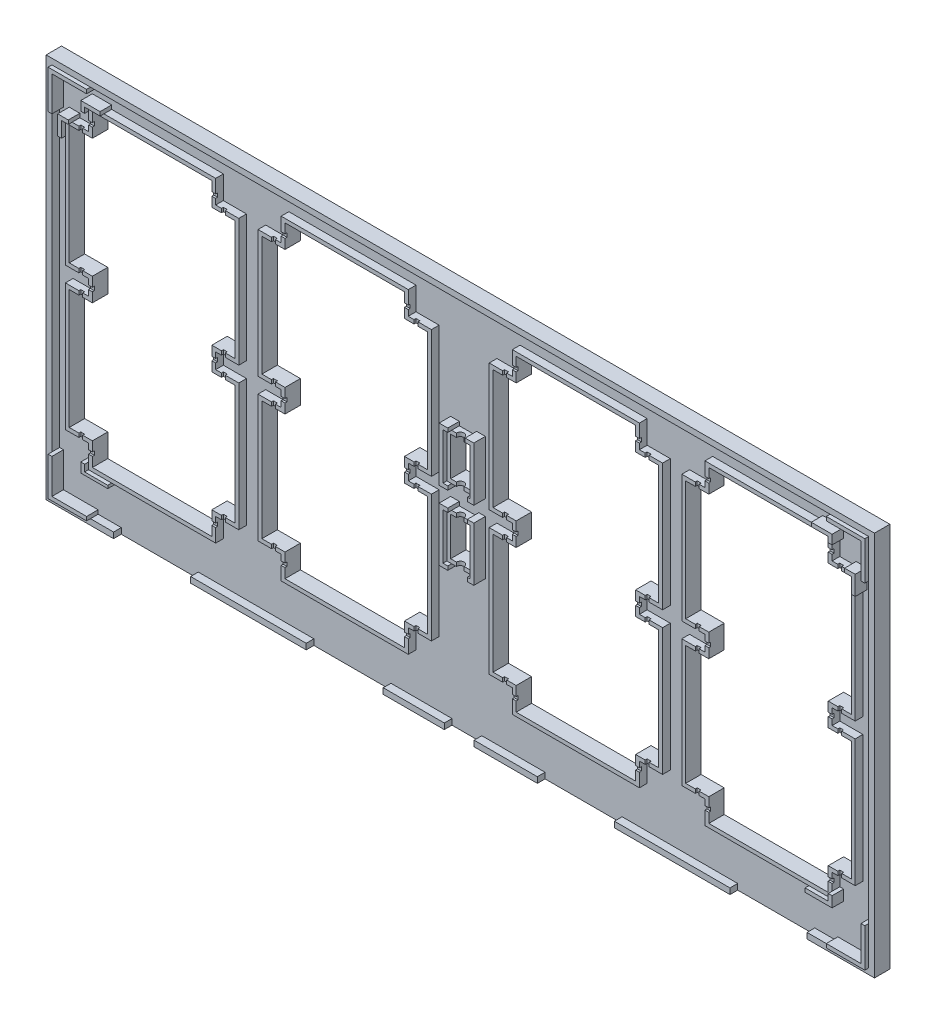
SolidWorks part; units mm, degrees
ref_plane "Спереди" through (0, 0, 0) normal (0, 0, 1) x (1, 0, 0)
ref_plane "Сверху" through (0, 0, 0) normal (0, 1, 0) x (1, 0, 0)
ref_plane "Справа" through (0, 0, 0) normal (1, 0, 0) x (0, 0, -1)
other "Configuration Table"
sketch "Эскиз1" plane through (0, 0, 0) normal (0, 0, 1) x (1, 0, 0)
  line L0 (0, 0) -> (210, 0)
  line L1 (210, 0) -> (210, 100)
  line L2 (210, 100) -> (0, 100)
  line L3 (0, 100) -> (0, 0)
  dimension "D1" = 210
  dimension "D2" = 100
extrude "Бобышка-Вытянуть1" add sketch "Эскиз1" along normal blind 2
sketch "Эскиз2" plane through (0, 0, 2) normal (0, 0, 1) x (1, 0, 0)
  line L4 (3.5, 56.2516) -> (9.5, 56.2516)
  line L5 (40.5, 87.2516) -> (46.5, 87.2516)
  line L6 (9.5, 56.2516) -> (9.5, 50.2516)
  line L7 (9.5, 93.2516) -> (9.5, 87.2516)
  line L9 (40.5, 87.2516) -> (40.5, 93.2516)
  line L10 (40.5, 93.2516) -> (9.5, 93.2516)
  line L11 (53.5, 56.2516) -> (59.5, 56.2516)
  line L12 (9.5, 19.2516) -> (9.5, 13.2516)
  line L13 (9.5, 13.2516) -> (40.5, 13.2516)
  line L14 (40.5, 13.2516) -> (40.5, 19.2516)
  line L16 (90.5, 87.2516) -> (96.5, 87.2516)
  line L20 (40.5, 56.2516) -> (40.5, 50.2516)
  line L21 (59.5, 56.2516) -> (59.5, 50.2516)
  line L22 (59.5, 93.2516) -> (59.5, 87.2516)
  line L23 (25, 93.2516) -> (25, 13.3713) construction
  line L24 (25, 56.2516) -> (25, 33.3628) construction
  line L25 (3.5, 50.2516) -> (3.5, 19.2516)
  line L26 (3.5, 19.2516) -> (9.5, 19.2516)
  line L28 (9.5, 50.2516) -> (3.5, 50.2516)
  line L30 (40.5, 56.2516) -> (46.5, 56.2516)
  line L31 (46.5, 56.2516) -> (46.5, 87.2516)
  line L33 (3.5, 87.2516) -> (3.5, 56.2516)
  line L36 (9.5, 87.2516) -> (3.5, 87.2516)
  line L38 (40.5, 19.2516) -> (46.5, 19.2516)
  line L39 (46.5, 19.2516) -> (46.5, 50.2516)
  line L40 (46.5, 50.2516) -> (40.5, 50.2516)
  line L41 (25, 19.2516) -> (25, 10.047) construction
  line L42 (6.5, 87.2516) -> (6.5, 54.1946) construction
  line L43 (0, 100) -> (0, 0) construction
  line L45 (90.5, 87.2516) -> (90.5, 93.2516)
  line L46 (90.5, 93.2516) -> (59.5, 93.2516)
  line L47 (59.5, 19.2516) -> (59.5, 13.2516)
  line L48 (59.5, 13.2516) -> (90.5, 13.2516)
  line L49 (90.5, 13.2516) -> (90.5, 19.2516)
  line L53 (90.5, 56.2516) -> (90.5, 50.2516)
  line L54 (53.5, 50.2516) -> (53.5, 19.2516)
  line L55 (53.5, 19.2516) -> (59.5, 19.2516)
  line L57 (59.5, 50.2516) -> (53.5, 50.2516)
  line L59 (90.5, 56.2516) -> (96.5, 56.2516)
  line L60 (96.5, 56.2516) -> (96.5, 87.2516)
  line L61 (53.5, 87.2516) -> (53.5, 56.2516)
  line L63 (59.5, 87.2516) -> (53.5, 87.2516)
  line L65 (90.5, 19.2516) -> (96.5, 19.2516)
  line L66 (96.5, 19.2516) -> (96.5, 50.2516)
  line L67 (96.5, 50.2516) -> (90.5, 50.2516)
  line L68 (75, 93.2516) -> (75, 13.3713) construction
  line L69 (75, 56.2516) -> (75, 33.3628) construction
  line L70 (75, 19.2516) -> (75, 10.047) construction
  line L71 (56.5, 87.2516) -> (56.5, 54.1946) construction
  line L72 (3.5, 56.2516) -> (9.5, 56.2516) construction
  line L73 (113.5, 56.2516) -> (119.5, 56.2516)
  line L74 (150.5, 87.2516) -> (156.5, 87.2516)
  line L75 (119.5, 56.2516) -> (119.5, 50.2516)
  line L76 (119.5, 93.2516) -> (119.5, 87.2516)
  line L78 (150.5, 87.2516) -> (150.5, 93.2516)
  line L79 (150.5, 93.2516) -> (119.5, 93.2516)
  line L80 (119.5, 19.2516) -> (119.5, 13.2516)
  line L81 (119.5, 13.2516) -> (150.5, 13.2516)
  line L82 (150.5, 13.2516) -> (150.5, 19.2516)
  line L86 (150.5, 56.2516) -> (150.5, 50.2516)
  line L87 (113.5, 50.2516) -> (113.5, 19.2516)
  line L88 (113.5, 19.2516) -> (119.5, 19.2516)
  line L90 (119.5, 50.2516) -> (113.5, 50.2516)
  line L92 (150.5, 56.2516) -> (156.5, 56.2516)
  line L93 (156.5, 56.2516) -> (156.5, 87.2516)
  line L94 (113.5, 87.2516) -> (113.5, 56.2516)
  line L96 (119.5, 87.2516) -> (113.5, 87.2516)
  line L98 (150.5, 19.2516) -> (156.5, 19.2516)
  line L99 (156.5, 19.2516) -> (156.5, 50.2516)
  line L100 (156.5, 50.2516) -> (150.5, 50.2516)
  line L101 (135, 93.2516) -> (135, 13.3713) construction
  line L102 (135, 56.2516) -> (135, 33.3628) construction
  line L103 (135, 19.2516) -> (135, 10.047) construction
  line L104 (116.5, 87.2516) -> (116.5, 54.1946) construction
  line L105 (90.5, 56.2516) -> (96.5, 56.2516) construction
  line L106 (53.5, 56.2516) -> (59.5, 56.2516) construction
  line L107 (163.5, 56.2516) -> (169.5, 56.2516)
  line L108 (200.5, 87.2516) -> (206.5, 87.2516)
  line L109 (169.5, 56.2516) -> (169.5, 50.2516)
  line L110 (169.5, 93.2516) -> (169.5, 87.2516)
  line L112 (200.5, 87.2516) -> (200.5, 93.2516)
  line L113 (200.5, 93.2516) -> (169.5, 93.2516)
  line L114 (169.5, 19.2516) -> (169.5, 13.2516)
  line L115 (169.5, 13.2516) -> (200.5, 13.2516)
  line L116 (200.5, 13.2516) -> (200.5, 19.2516)
  line L120 (200.5, 56.2516) -> (200.5, 50.2516)
  line L121 (163.5, 50.2516) -> (163.5, 19.2516)
  line L122 (163.5, 19.2516) -> (169.5, 19.2516)
  line L124 (169.5, 50.2516) -> (163.5, 50.2516)
  line L126 (200.5, 56.2516) -> (206.5, 56.2516)
  line L127 (206.5, 56.2516) -> (206.5, 87.2516)
  line L128 (163.5, 87.2516) -> (163.5, 56.2516)
  line L130 (169.5, 87.2516) -> (163.5, 87.2516)
  line L132 (200.5, 19.2516) -> (206.5, 19.2516)
  line L133 (206.5, 19.2516) -> (206.5, 50.2516)
  line L134 (206.5, 50.2516) -> (200.5, 50.2516)
  line L135 (185, 93.2516) -> (185, 13.3713) construction
  line L136 (185, 56.2516) -> (185, 33.3628) construction
  line L137 (185, 19.2516) -> (185, 10.047) construction
  line L138 (166.5, 87.2516) -> (166.5, 54.1946) construction
  line L139 (113.5, 56.2516) -> (119.5, 56.2516) construction
  line L140 (113.5, 56.2516) -> (119.5, 56.2516) construction
  line L141 (113.5, 56.2516) -> (119.5, 56.2516) construction
  line L142 (40.5, 56.2516) -> (46.5, 56.2516) construction
  line L143 (90.5, 56.2516) -> (96.5, 56.2516) construction
  line L144 (150.5, 56.2516) -> (156.5, 56.2516) construction
  line L145 (150.5, 56.2516) -> (156.5, 56.2516) construction
  line L146 (150.5, 56.2516) -> (156.5, 56.2516) construction
  point P0 (0, 0)
  dimension "D3" = 25
  dimension "D4" = 25
  dimension "D5" = 2
  dimension "D6" = 31
  dimension "D7" = 31
  dimension "D8" = 18.5
  dimension "D9" = 6
  dimension "D10" = 6
  dimension "D12" = 2
  dimension "D13" = 60
  dimension "D14" = 2
  dimension "D15" = 31
  dimension "D16" = 6
  dimension "D23" = 6
  dimension "D24" = 6
  dimension "D25" = 6
extrude "Вырез-Вытянуть1" cut sketch "Эскиз2" against normal blind 2 contours L11 L21 L57 L54 L55 L47 L48 L49 L65 L66 L67 L53 L59 L60 L16 L45 L46 L22 L63 L61 | L96 L94 L73 L75 L90 L87 L88 L80 L81 L82 L98 L99 L100 L86 L92 L93 L74 L78 L79 L76 | L12 L13 L14 L38 L39 L40 L20 L30 L31 L5 L9 L10 L7 L36 L33 L4 L6 L28 L25 L26 | L120 L126 L127 L108 L112 L113 L110 L130 L128 L107 L109 L124 L121 L122 L114 L115 L116 L132 L133 L134
sketch "Эскиз3" plane through (0, 0, 2) normal (0, 0, 1) x (1, 0, 0)
  line L0 (105, 100) -> (105, 0) construction
  line L1 (210, 100) -> (0, 100) construction
  line L2 (0, 0) -> (210, 0) construction
  line L3 (102.5, 67.2516) -> (107.5, 67.2516)
  line L4 (107.5, 67.2516) -> (107.5, 57.2516)
  line L5 (107.5, 57.2516) -> (102.5, 57.2516)
  line L6 (102.5, 57.2516) -> (102.5, 67.2516)
  line L7 (102.5, 49.2516) -> (102.5, 39.2516)
  line L8 (102.5, 39.2516) -> (107.5, 39.2516)
  line L10 (107.5, 49.2516) -> (102.5, 49.2516)
  line L11 (107.5, 49.2516) -> (107.5, 39.2516)
  line L13 (113.5, 56.2516) -> (119.5, 56.2516) construction
  point P14 (107.5, 62.2516)
  dimension "D1" = 10
  dimension "D2" = 5
  dimension "D3" = 5
  dimension "D4" = 10
  dimension "D5" = 2.5
  dimension "D6" = 8
  dimension "D7" = 1
extrude "Вырез-Вытянуть2" cut sketch "Эскиз3" against normal blind 2
sketch "Эскиз5" plane through (0, 0, 2) normal (0, 0, 1) x (1, 0, 0)
  line L0 (9.5, 93.2516) -> (40.5, 93.2516)
  line L1 (40.5, 93.2516) -> (40.5, 87.2516)
  line L2 (40.5, 87.2516) -> (46.5, 87.2516)
  line L3 (46.5, 87.2516) -> (46.5, 56.2516)
  line L4 (46.5, 56.2516) -> (40.5, 56.2516)
  line L5 (40.5, 56.2516) -> (40.5, 50.2516)
  line L6 (40.5, 50.2516) -> (46.5, 50.2516)
  line L7 (46.5, 50.2516) -> (46.5, 19.2516)
  line L8 (46.5, 19.2516) -> (40.5, 19.2516)
  line L9 (40.5, 19.2516) -> (40.5, 13.2516)
  line L10 (40.5, 13.2516) -> (9.5, 13.2516)
  line L11 (9.5, 13.2516) -> (9.5, 19.2516)
  line L12 (9.5, 19.2516) -> (3.5, 19.2516)
  line L13 (3.5, 19.2516) -> (3.5, 50.2516)
  line L14 (3.5, 50.2516) -> (9.5, 50.2516)
  line L15 (9.5, 50.2516) -> (9.5, 56.2516)
  line L16 (9.5, 56.2516) -> (3.5, 56.2516)
  line L17 (3.5, 56.2516) -> (3.5, 87.2516)
  line L18 (3.5, 87.2516) -> (9.5, 87.2516)
  line L19 (9.5, 87.2516) -> (9.5, 93.2516)
  line L20 (8.5, 88.2516) -> (8.5, 94.2516)
  line L21 (8.5, 94.2516) -> (41.5, 94.2516)
  line L22 (41.5, 94.2516) -> (41.5, 88.2516)
  line L23 (41.5, 88.2516) -> (47.5, 88.2516)
  line L24 (47.5, 88.2516) -> (47.5, 55.2516)
  line L25 (47.5, 55.2516) -> (41.5, 55.2516)
  line L26 (41.5, 55.2516) -> (41.5, 51.2516)
  line L27 (41.5, 51.2516) -> (47.5, 51.2516)
  line L28 (47.5, 51.2516) -> (47.5, 18.2516)
  line L29 (47.5, 18.2516) -> (41.5, 18.2516)
  line L30 (41.5, 18.2516) -> (41.5, 12.2516)
  line L31 (41.5, 12.2516) -> (8.5, 12.2516)
  line L32 (8.5, 12.2516) -> (8.5, 18.2516)
  line L33 (8.5, 18.2516) -> (2.5, 18.2516)
  line L34 (2.5, 18.2516) -> (2.5, 51.2516)
  line L35 (2.5, 51.2516) -> (8.5, 51.2516)
  line L36 (8.5, 51.2516) -> (8.5, 55.2516)
  line L37 (8.5, 55.2516) -> (2.5, 55.2516)
  line L38 (2.5, 55.2516) -> (2.5, 88.2516)
  line L39 (2.5, 88.2516) -> (8.5, 88.2516)
  dimension "D1" = 1
extrude "Бобышка-Вытянуть3" add sketch "Эскиз5" along normal blind 2
sketch "Эскиз6" plane through (0, 0, 2) normal (0, 0, 1) x (1, 0, 0)
  line L0 (59.5, 93.2516) -> (90.5, 93.2516)
  line L1 (90.5, 93.2516) -> (90.5, 87.2516)
  line L2 (90.5, 87.2516) -> (96.5, 87.2516)
  line L3 (96.5, 87.2516) -> (96.5, 56.2516)
  line L4 (96.5, 56.2516) -> (90.5, 56.2516)
  line L5 (90.5, 56.2516) -> (90.5, 50.2516)
  line L6 (90.5, 50.2516) -> (96.5, 50.2516)
  line L7 (96.5, 50.2516) -> (96.5, 19.2516)
  line L8 (96.5, 19.2516) -> (90.5, 19.2516)
  line L9 (90.5, 19.2516) -> (90.5, 13.2516)
  line L10 (90.5, 13.2516) -> (59.5, 13.2516)
  line L11 (59.5, 13.2516) -> (59.5, 19.2516)
  line L12 (59.5, 19.2516) -> (53.5, 19.2516)
  line L13 (53.5, 19.2516) -> (53.5, 50.2516)
  line L14 (53.5, 50.2516) -> (59.5, 50.2516)
  line L15 (59.5, 50.2516) -> (59.5, 56.2516)
  line L16 (53.5, 56.2516) -> (59.5, 56.2516) construction
  line L17 (59.5, 56.2516) -> (59.5, 50.2516) construction
  line L18 (59.5, 56.2516) -> (53.5, 56.2516)
  line L19 (53.5, 56.2516) -> (53.5, 87.2516)
  line L20 (53.5, 87.2516) -> (59.5, 87.2516)
  line L21 (59.5, 87.2516) -> (59.5, 93.2516)
  line L22 (58.5, 88.2516) -> (58.5, 94.2516)
  line L23 (58.5, 94.2516) -> (91.5, 94.2516)
  line L24 (91.5, 94.2516) -> (91.5, 88.2516)
  line L25 (91.5, 88.2516) -> (97.5, 88.2516)
  line L26 (97.5, 88.2516) -> (97.5, 55.2516)
  line L27 (97.5, 55.2516) -> (91.5, 55.2516)
  line L28 (91.5, 55.2516) -> (91.5, 51.2516)
  line L29 (91.5, 51.2516) -> (97.5, 51.2516)
  line L30 (97.5, 51.2516) -> (97.5, 18.2516)
  line L31 (97.5, 18.2516) -> (91.5, 18.2516)
  line L32 (91.5, 18.2516) -> (91.5, 12.2516)
  line L33 (91.5, 12.2516) -> (58.5, 12.2516)
  line L34 (58.5, 12.2516) -> (58.5, 18.2516)
  line L35 (58.5, 18.2516) -> (52.5, 18.2516)
  line L36 (52.5, 18.2516) -> (52.5, 51.2516)
  line L37 (52.5, 51.2516) -> (58.5, 51.2516)
  line L38 (58.5, 51.2516) -> (58.5, 55.2516)
  line L39 (58.5, 55.2516) -> (52.5, 55.2516)
  line L40 (52.5, 55.2516) -> (52.5, 88.2516)
  line L41 (52.5, 88.2516) -> (58.5, 88.2516)
  dimension "D1" = 1
extrude "Бобышка-Вытянуть4" add sketch "Эскиз6" along normal blind 2
sketch "Эскиз7" plane through (0, 0, 2) normal (0, 0, 1) x (1, 0, 0)
  line L0 (0, 100) -> (-2.5, 100)
  line L1 (-2.5, 100) -> (-2.5, 0)
  line L2 (-2.5, 0) -> (0, 0)
  line L3 (0, 0) -> (0, 100)
  dimension "D1" = 2.5
extrude "Бобышка-Вытянуть5" add sketch "Эскиз7" against normal blind 2
sketch "Эскиз8" plane through (0, 0, 2) normal (0, 0, 1) x (1, 0, 0)
  line L0 (210, 100) -> (212.5, 100)
  line L1 (212.5, 100) -> (212.5, 0)
  line L2 (212.5, 0) -> (210, 0)
  line L3 (210, 0) -> (210, 100)
  dimension "D1" = 2.5
extrude "Бобышка-Вытянуть6" add sketch "Эскиз8" against normal blind 2
sketch "Эскиз9" plane through (0, 0, 2) normal (0, 0, 1) x (1, 0, 0)
  line L0 (102.5, 67.2516) -> (107.5, 67.2516)
  line L1 (107.5, 67.2516) -> (107.5, 57.2516)
  line L2 (107.5, 57.2516) -> (102.5, 57.2516)
  line L3 (102.5, 57.2516) -> (102.5, 67.2516)
  line L4 (101.5, 56.2516) -> (101.5, 68.2516)
  line L5 (101.5, 68.2516) -> (108.5, 68.2516)
  line L6 (108.5, 68.2516) -> (108.5, 56.2516)
  line L7 (108.5, 56.2516) -> (101.5, 56.2516)
  dimension "D1" = 1
extrude "Бобышка-Вытянуть7" add sketch "Эскиз9" along normal blind 2
sketch "Эскиз10" plane through (0, 0, 2) normal (0, 0, 1) x (1, 0, 0)
  line L0 (102.5, 49.2516) -> (107.5, 49.2516)
  line L1 (107.5, 49.2516) -> (107.5, 39.2516)
  line L2 (107.5, 39.2516) -> (102.5, 39.2516)
  line L3 (102.5, 39.2516) -> (102.5, 49.2516)
  line L4 (101.5, 38.2516) -> (101.5, 50.2516)
  line L5 (101.5, 50.2516) -> (108.5, 50.2516)
  line L6 (108.5, 50.2516) -> (108.5, 38.2516)
  line L7 (108.5, 38.2516) -> (101.5, 38.2516)
  dimension "D1" = 1
extrude "Бобышка-Вытянуть8" add sketch "Эскиз10" along normal blind 2
sketch "Эскиз11" plane through (0, 0, 2) normal (0, 0, 1) x (1, 0, 0)
  line L0 (119.5, 93.2516) -> (150.5, 93.2516)
  line L1 (150.5, 93.2516) -> (150.5, 87.2516)
  line L2 (150.5, 87.2516) -> (156.5, 87.2516)
  line L3 (156.5, 87.2516) -> (156.5, 56.2516)
  line L4 (156.5, 56.2516) -> (150.5, 56.2516)
  line L5 (150.5, 56.2516) -> (150.5, 50.2516)
  line L6 (150.5, 50.2516) -> (156.5, 50.2516)
  line L7 (156.5, 50.2516) -> (156.5, 19.2516)
  line L8 (156.5, 19.2516) -> (150.5, 19.2516)
  line L9 (150.5, 19.2516) -> (150.5, 13.2516)
  line L10 (150.5, 13.2516) -> (119.5, 13.2516)
  line L11 (119.5, 13.2516) -> (119.5, 19.2516)
  line L12 (119.5, 19.2516) -> (113.5, 19.2516)
  line L13 (113.5, 19.2516) -> (113.5, 50.2516)
  line L14 (113.5, 50.2516) -> (119.5, 50.2516)
  line L15 (119.5, 50.2516) -> (119.5, 56.2516)
  line L16 (119.5, 56.2516) -> (113.5, 56.2516)
  line L17 (113.5, 56.2516) -> (113.5, 87.2516)
  line L18 (113.5, 87.2516) -> (119.5, 87.2516)
  line L19 (119.5, 87.2516) -> (119.5, 93.2516)
  line L20 (118.5, 88.2516) -> (118.5, 94.2516)
  line L21 (118.5, 94.2516) -> (151.5, 94.2516)
  line L22 (151.5, 94.2516) -> (151.5, 88.2516)
  line L23 (151.5, 88.2516) -> (157.5, 88.2516)
  line L24 (157.5, 88.2516) -> (157.5, 55.2516)
  line L25 (157.5, 55.2516) -> (151.5, 55.2516)
  line L26 (151.5, 55.2516) -> (151.5, 51.2516)
  line L27 (151.5, 51.2516) -> (157.5, 51.2516)
  line L28 (157.5, 51.2516) -> (157.5, 18.2516)
  line L29 (157.5, 18.2516) -> (151.5, 18.2516)
  line L30 (151.5, 18.2516) -> (151.5, 12.2516)
  line L31 (151.5, 12.2516) -> (118.5, 12.2516)
  line L32 (118.5, 12.2516) -> (118.5, 18.2516)
  line L33 (118.5, 18.2516) -> (112.5, 18.2516)
  line L34 (112.5, 18.2516) -> (112.5, 51.2516)
  line L35 (112.5, 51.2516) -> (118.5, 51.2516)
  line L36 (118.5, 51.2516) -> (118.5, 55.2516)
  line L37 (118.5, 55.2516) -> (112.5, 55.2516)
  line L38 (112.5, 55.2516) -> (112.5, 88.2516)
  line L39 (112.5, 88.2516) -> (118.5, 88.2516)
  dimension "D1" = 1
extrude "Бобышка-Вытянуть9" add sketch "Эскиз11" along normal blind 2
sketch "Эскиз12" plane through (0, 0, 2) normal (0, 0, 1) x (1, 0, 0)
  line L0 (169.5, 93.2516) -> (200.5, 93.2516)
  line L1 (200.5, 93.2516) -> (200.5, 87.2516)
  line L2 (200.5, 87.2516) -> (206.5, 87.2516)
  line L3 (206.5, 87.2516) -> (206.5, 56.2516)
  line L4 (206.5, 56.2516) -> (200.5, 56.2516)
  line L5 (200.5, 56.2516) -> (200.5, 50.2516)
  line L6 (200.5, 50.2516) -> (206.5, 50.2516)
  line L7 (206.5, 50.2516) -> (206.5, 19.2516)
  line L8 (206.5, 19.2516) -> (200.5, 19.2516)
  line L9 (200.5, 19.2516) -> (200.5, 13.2516)
  line L10 (200.5, 13.2516) -> (169.5, 13.2516)
  line L11 (169.5, 13.2516) -> (169.5, 19.2516)
  line L12 (169.5, 19.2516) -> (163.5, 19.2516)
  line L13 (163.5, 19.2516) -> (163.5, 50.2516)
  line L14 (163.5, 50.2516) -> (169.5, 50.2516)
  line L15 (169.5, 50.2516) -> (169.5, 56.2516)
  line L16 (163.5, 56.2516) -> (169.5, 56.2516) construction
  line L17 (169.5, 56.2516) -> (169.5, 50.2516) construction
  line L18 (169.5, 56.2516) -> (163.5, 56.2516)
  line L19 (163.5, 56.2516) -> (163.5, 87.2516)
  line L20 (163.5, 87.2516) -> (169.5, 87.2516)
  line L21 (169.5, 87.2516) -> (169.5, 93.2516)
  line L22 (168.5, 88.2516) -> (168.5, 94.2516)
  line L23 (168.5, 94.2516) -> (201.5, 94.2516)
  line L24 (201.5, 94.2516) -> (201.5, 88.2516)
  line L25 (201.5, 88.2516) -> (207.5, 88.2516)
  line L26 (207.5, 88.2516) -> (207.5, 55.2516)
  line L27 (207.5, 55.2516) -> (201.5, 55.2516)
  line L28 (201.5, 55.2516) -> (201.5, 51.2516)
  line L29 (201.5, 51.2516) -> (207.5, 51.2516)
  line L30 (207.5, 51.2516) -> (207.5, 18.2516)
  line L31 (207.5, 18.2516) -> (201.5, 18.2516)
  line L32 (201.5, 18.2516) -> (201.5, 12.2516)
  line L33 (201.5, 12.2516) -> (168.5, 12.2516)
  line L34 (168.5, 12.2516) -> (168.5, 18.2516)
  line L35 (168.5, 18.2516) -> (162.5, 18.2516)
  line L36 (162.5, 18.2516) -> (162.5, 51.2516)
  line L37 (162.5, 51.2516) -> (168.5, 51.2516)
  line L38 (168.5, 51.2516) -> (168.5, 55.2516)
  line L39 (168.5, 55.2516) -> (162.5, 55.2516)
  line L40 (162.5, 55.2516) -> (162.5, 88.2516)
  line L41 (162.5, 88.2516) -> (168.5, 88.2516)
  dimension "D1" = 1
extrude "Бобышка-Вытянуть10" add sketch "Эскиз12" along normal blind 2
sketch "Эскиз13" plane through (0, 0, 2) normal (0, 0, 1) x (1, 0, 0)
  line L0 (-1, 98.5) -> (211, 98.5)
  line L1 (-2.5, 100) -> (212.5, 100)
  line L2 (212.5, 100) -> (212.5, 0)
  line L3 (212.5, 0) -> (-2.5, 0)
  line L4 (-2.5, 0) -> (-2.5, 100)
  line L5 (211, 98.5) -> (211, 1.5)
  line L6 (211, 1.5) -> (-1, 1.5)
  line L7 (-1, 1.5) -> (-1, 98.5)
  dimension "D1" = 1.5
extrude "Бобышка-Вытянуть12" add sketch "Эскиз13" along normal blind 2
sketch "Эскиз15" plane through (0, 0, 4) normal (0, 0, 1) x (1, 0, 0)
  line L0 (6.5, 87.2516) -> (6.5, 19.2516) construction
  line L1 (9.5, 87.2516) -> (3.5, 87.2516) construction
  line L2 (3.5, 19.2516) -> (9.5, 19.2516) construction
  line L3 (7, 87.8467) -> (7, 16.4283)
  line L4 (7, 16.4283) -> (6, 16.4283)
  line L5 (6, 16.4283) -> (6, 89.7154)
  line L6 (6, 89.7154) -> (7, 89.7154)
  line L7 (7, 89.7154) -> (7, 87.8467)
  dimension "D1" = 0.5
  dimension "D2" = 0.5
extrude "Вырез-Вытянуть5" cut sketch "Эскиз15" against normal blind 0.5
sketch "Эскиз16" plane through (0, 0, 4) normal (0, 0, 1) x (1, 0, 0)
  line L0 (9.5, 53.2516) -> (202.9622, 53.2516) construction
  line L1 (9.5, 56.2516) -> (9.5, 50.2516) construction
  line L2 (9.5, 53.7516) -> (207.2357, 53.7516)
  line L3 (207.2357, 53.7516) -> (207.2357, 52.7516)
  line L4 (207.2357, 52.7516) -> (7.0331, 52.7516)
  line L5 (7.0331, 52.7516) -> (7.0331, 53.7516)
  line L6 (7.0331, 53.7516) -> (9.5, 53.7516)
  dimension "D1" = 0.5
  dimension "D2" = 0.5
extrude "Вырез-Вытянуть6" cut sketch "Эскиз16" against normal blind 0.5
sketch "Эскиз18" plane through (0, 38.2516, 0) normal (0, -1, 0) x (1, 0, 0)
  line L0 (-2.5, 4) -> (212.5, 4) construction
  circle A0 centre (105, 4) radius 1
extrude "Вырез-Вытянуть8" cut sketch "Эскиз18" against normal blind 40
sketch "Эскиз19" plane through (0, 0, 4) normal (0, 0, 1) x (1, 0, 0)
  line L0 (9.5, 16.2516) -> (200.5, 16.2516) construction
  line L1 (9.5, 19.2516) -> (9.5, 13.2516) construction
  line L2 (200.5, 13.2516) -> (200.5, 19.2516) construction
  line L3 (9.5, 16.7516) -> (205.6371, 16.7516)
  line L4 (205.6371, 16.7516) -> (205.6371, 15.7516)
  line L5 (205.6371, 15.7516) -> (6.3461, 15.7516)
  line L6 (6.3461, 15.7516) -> (6.3461, 16.7516)
  line L7 (6.3461, 16.7516) -> (9.5, 16.7516)
  dimension "D1" = 0.5
  dimension "D2" = 0.5
extrude "Вырез-Вытянуть9" cut sketch "Эскиз19" against normal blind 0.5
sketch "Эскиз20" plane through (0, 0, 4) normal (0, 0, 1) x (1, 0, 0)
  line L0 (9.5, 90.2516) -> (204.4151, 90.2516) construction
  line L1 (9.5, 93.2516) -> (9.5, 87.2516) construction
  line L2 (9.5, 90.7516) -> (205.9858, 90.7516)
  line L3 (205.9858, 90.7516) -> (205.9858, 89.7516)
  line L4 (205.9858, 89.7516) -> (6.902, 89.7516)
  line L5 (6.902, 89.7516) -> (6.902, 90.7516)
  line L6 (6.902, 90.7516) -> (9.5, 90.7516)
  dimension "D1" = 0.5
  dimension "D2" = 0.5
extrude "Вырез-Вытянуть10" cut sketch "Эскиз20" against normal blind 0.5
sketch "Эскиз21" plane through (0, 0, 4) normal (0, 0, 1) x (1, 0, 0)
  line L0 (43.5, 19.2516) -> (43.5, 87.2516) construction
  line L1 (40.5, 19.2516) -> (46.5, 19.2516) construction
  line L2 (46.5, 87.2516) -> (40.5, 87.2516) construction
  line L3 (44, 87.2516) -> (44, 14.6693)
  line L4 (44, 14.6693) -> (43, 14.6693)
  line L5 (43, 14.6693) -> (43, 89.404)
  line L6 (43, 89.404) -> (44, 89.404)
  line L7 (44, 89.404) -> (44, 87.2516)
  dimension "D1" = 0.5
  dimension "D2" = 0.5
extrude "Вырез-Вытянуть11" cut sketch "Эскиз21" against normal blind 0.5
sketch "Эскиз22" plane through (0, 0, 4) normal (0, 0, 1) x (1, 0, 0)
  line L0 (56.5, 87.2516) -> (56.5, 19.2516) construction
  line L1 (59.5, 87.2516) -> (53.5, 87.2516) construction
  line L2 (53.5, 19.2516) -> (59.5, 19.2516) construction
  line L3 (57, 87.2516) -> (57, 16.867)
  line L4 (57, 16.867) -> (56, 16.867)
  line L5 (56, 16.867) -> (56, 91.2358)
  line L6 (56, 91.2358) -> (57, 91.2358)
  line L7 (57, 91.2358) -> (57, 87.2516)
  dimension "D1" = 0.5
  dimension "D2" = 0.5
extrude "Вырез-Вытянуть12" cut sketch "Эскиз22" against normal blind 0.5
sketch "Эскиз23" plane through (0, 0, 4) normal (0, 0, 1) x (1, 0, 0)
  line L0 (93.5, 87.2516) -> (93.5, 19.2516) construction
  line L1 (96.5, 87.2516) -> (90.5, 87.2516) construction
  line L2 (90.5, 19.2516) -> (96.5, 19.2516) construction
  line L3 (94, 19.2516) -> (94, 90.8274)
  line L4 (94, 90.8274) -> (93, 90.8274)
  line L5 (93, 90.8274) -> (93, 16.2231)
  line L6 (93, 16.2231) -> (94, 16.2231)
  line L7 (94, 16.2231) -> (94, 19.2516)
  dimension "D1" = 0.5
  dimension "D2" = 0.5
extrude "Вырез-Вытянуть13" cut sketch "Эскиз23" against normal blind 0.5
sketch "Эскиз24" plane through (0, 0, 4) normal (0, 0, 1) x (1, 0, 0)
  line L0 (116.5, 87.2516) -> (116.5, 19.2516) construction
  line L1 (119.5, 87.2516) -> (113.5, 87.2516) construction
  line L2 (113.5, 19.2516) -> (119.5, 19.2516) construction
  line L3 (116, 19.2516) -> (116, 17.2818)
  line L4 (116, 17.2818) -> (117, 17.2818)
  line L5 (117, 17.2818) -> (117, 91.1115)
  line L6 (117, 91.1115) -> (116, 91.1115)
  line L7 (116, 91.1115) -> (116, 19.2516)
  dimension "D1" = 0.5
  dimension "D2" = 0.5
extrude "Вырез-Вытянуть14" cut sketch "Эскиз24" against normal blind 0.5
sketch "Эскиз25" plane through (0, 0, 4) normal (0, 0, 1) x (1, 0, 0)
  line L0 (153.5, 87.2516) -> (153.5, 19.2516) construction
  line L1 (156.5, 87.2516) -> (150.5, 87.2516) construction
  line L2 (150.5, 19.2516) -> (156.5, 19.2516) construction
  line L3 (154, 19.2516) -> (154, 16.4787)
  line L4 (154, 16.4787) -> (153, 16.4787)
  line L5 (153, 16.4787) -> (153, 93.5281)
  line L7 (153, 93.5281) -> (154, 93.5281)
  line L8 (154, 93.5281) -> (154, 19.2516)
  dimension "D1" = 0.5
  dimension "D2" = 0.5
extrude "Вырез-Вытянуть15" cut sketch "Эскиз25" against normal blind 0.5
sketch "Эскиз26" plane through (0, 0, 4) normal (0, 0, 1) x (1, 0, 0)
  line L0 (166.5, 19.2516) -> (166.5, 87.2516) construction
  line L1 (163.5, 19.2516) -> (169.5, 19.2516) construction
  line L2 (169.5, 87.2516) -> (163.5, 87.2516) construction
  line L3 (167, 87.2516) -> (167, 89.7461)
  line L4 (167, 89.7461) -> (166, 89.7461)
  line L5 (166, 89.7461) -> (166, 15.4759)
  line L6 (166, 15.4759) -> (167, 15.4759)
  line L7 (167, 15.4759) -> (167, 87.2516)
  dimension "D1" = 0.5
  dimension "D2" = 0.5
extrude "Вырез-Вытянуть16" cut sketch "Эскиз26" against normal blind 0.5
sketch "Эскиз27" plane through (0, 0, 4) normal (0, 0, 1) x (1, 0, 0)
  line L0 (203.5, 87.2516) -> (203.5, 19.2516) construction
  line L1 (206.5, 87.2516) -> (200.5, 87.2516) construction
  line L2 (200.5, 19.2516) -> (206.5, 19.2516) construction
  line L3 (204, 19.2516) -> (204, 15.5041)
  line L4 (204, 15.5041) -> (203, 15.5041)
  line L5 (203, 15.5041) -> (203, 91.2528)
  line L6 (203, 91.2528) -> (204, 91.2528)
  line L7 (204, 91.2528) -> (204, 19.2516)
  dimension "D1" = 0.5
  dimension "D2" = 0.5
extrude "Вырез-Вытянуть17" cut sketch "Эскиз27" against normal blind 0.5
sketch "Эскиз28" plane through (0, 0, 2) normal (0, 0, 1) x (1, 0, 0)
  line L0 (15, 3.5631) -> (15, -1.5784)
  line L1 (15, -1.5784) -> (35, -1.5784)
  line L2 (35, -1.5784) -> (35, 3.5631)
  line L3 (35, 3.5631) -> (15, 3.5631)
  line L4 (25, 12.2516) -> (25, 24.8241) construction
  line L5 (8.5, 12.2516) -> (41.5, 12.2516) construction
  line L6 (65, 3.5631) -> (65, -1.5784)
  line L7 (65, -1.5784) -> (85, -1.5784)
  line L8 (85, -1.5784) -> (85, 3.5631)
  line L9 (85, 3.5631) -> (65, 3.5631)
  line L10 (15, 3.5631) -> (65, 3.5631) construction
  line L11 (125, 3.5631) -> (125, -1.5784)
  line L12 (125, -1.5784) -> (145, -1.5784)
  line L13 (145, -1.5784) -> (145, 3.5631)
  line L14 (145, 3.5631) -> (125, 3.5631)
  line L15 (65, 3.5631) -> (125, 3.5631) construction
  line L16 (175, 3.5631) -> (175, -1.5784)
  line L17 (175, -1.5784) -> (195, -1.5784)
  line L18 (195, -1.5784) -> (195, 3.5631)
  line L19 (195, 3.5631) -> (175, 3.5631)
  line L20 (125, 3.5631) -> (175, 3.5631) construction
  point P8 (15, 0.9923)
  dimension "D1" = 20
  dimension "D2" = 10
  dimension "D4" = 50
  dimension "D6" = 60
  dimension "D8" = 50
  dimension "D3" = 2
  dimension "D5" = 2
  dimension "D7" = 2
extrude "Вырез-Вытянуть18" cut sketch "Эскиз28" along normal blind 2
sketch "Эскиз29" plane through (0, 0, 2) normal (0, 0, 1) x (1, 0, 0)
  line L0 (100.8505, 3.1793) -> (100.8505, -1.589)
  line L1 (100.8505, -1.589) -> (108.5858, -1.589)
  line L2 (108.5858, -1.589) -> (108.5858, 3.1793)
  line L3 (108.5858, 3.1793) -> (100.8505, 3.1793)
extrude "Вырез-Вытянуть19" cut sketch "Эскиз29" along normal blind 2
sketch "Эскиз30" plane through (0, 0, 2) normal (0, 0, 1) x (1, 0, 0)
  line L0 (-1, 98.5) -> (9, 98.5)
  line L1 (211, 98.5) -> (-1, 98.5) construction
  line L2 (9, 98.5) -> (9, 97.5)
  line L3 (9, 97.5) -> (0, 97.5)
  line L4 (0, 97.5) -> (0, 88.5)
  line L5 (0, 88.5) -> (-1, 88.5)
  line L6 (-1, 98.5) -> (-1, 1.5) construction
  line L7 (-1, 88.5) -> (-1, 98.5)
  line L8 (8.5, 94.2516) -> (12.5, 94.2516)
  line L9 (41.5, 94.2516) -> (8.5, 94.2516) construction
  line L10 (12.5, 94.2516) -> (12.5, 95.2516)
  line L11 (12.5, 95.2516) -> (7.5, 95.2516)
  line L12 (7.5, 95.2516) -> (7.5, 92.8466)
  line L13 (7.5, 92.8466) -> (8.5, 92.8466)
  line L14 (8.5, 94.2516) -> (8.5, 88.2516) construction
  line L15 (8.5, 92.8466) -> (8.5, 94.2516)
  line L16 (2.5, 88.2516) -> (4.25, 88.2516)
  line L17 (6, 88.2516) -> (2.5, 88.2516) construction
  line L18 (4.25, 88.2516) -> (4.25, 89.2516)
  line L19 (4.25, 89.2516) -> (1.5, 89.2516)
  line L20 (1.5, 89.2516) -> (1.5, 84.2516)
  line L21 (1.5, 84.2516) -> (2.5, 84.2516)
  line L22 (2.5, 88.2516) -> (2.5, 55.2516) construction
  line L23 (2.5, 84.2516) -> (2.5, 88.2516)
  line L24 (-1, 1.5) -> (9, 1.5)
  line L25 (-1, 1.5) -> (15, 1.5) construction
  line L26 (9, 1.5) -> (9, 2.5)
  line L27 (9, 2.5) -> (0, 2.5)
  line L28 (0, 2.5) -> (0, 11.5)
  line L29 (0, 11.5) -> (-1, 11.5)
  line L30 (-1, 98.5) -> (-1, 1.5) construction
  line L31 (-1, 11.5) -> (-1, 1.5)
  line L32 (8.5, 14.0016) -> (7.5, 14.0016)
  line L33 (8.5, 15.7516) -> (8.5, 12.2516) construction
  line L34 (7.5, 14.0016) -> (7.5, 11.5016)
  line L35 (7.5, 11.5016) -> (14.5, 11.5016)
  line L36 (14.5, 11.5016) -> (14.5, 12.2516)
  line L37 (8.5, 12.2516) -> (41.5, 12.2516) construction
  line L38 (14.5, 12.2516) -> (8.5, 12.2516)
  line L39 (8.5, 12.2516) -> (8.5, 14.0016)
  line L40 (211, 98.5) -> (211, 88.5)
  line L41 (211, 1.5) -> (211, 98.5) construction
  line L42 (211, 88.5) -> (210, 88.5)
  line L43 (210, 88.5) -> (210, 97.5)
  line L44 (210, 97.5) -> (201, 97.5)
  line L45 (201, 97.5) -> (201, 98.5)
  line L46 (211, 98.5) -> (-1, 98.5) construction
  line L47 (201, 98.5) -> (211, 98.5)
  line L48 (197.0985, 94.2516) -> (197.0985, 95.2516)
  line L49 (201.5, 94.2516) -> (168.5, 94.2516) construction
  line L50 (197.0985, 95.2516) -> (202.5, 95.2516)
  line L51 (202.5, 95.2516) -> (202.5, 92.8516)
  line L52 (197.0985, 94.2516) -> (201.5, 94.2516)
  line L54 (201.5, 94.2516) -> (201.5, 92.8516)
  line L55 (201.5, 88.2516) -> (201.5, 94.2516) construction
  line L56 (201.5, 92.8516) -> (202.5, 92.8516)
  line L57 (205.75, 88.2516) -> (205.75, 89.2516)
  line L58 (207.5, 88.2516) -> (204, 88.2516) construction
  line L59 (205.75, 89.2516) -> (208.5, 89.2516)
  line L60 (208.5, 89.2516) -> (208.5, 84.2516)
  line L61 (208.5, 84.2516) -> (207.5, 84.2516)
  line L62 (207.5, 55.2516) -> (207.5, 88.2516) construction
  line L63 (207.5, 84.2516) -> (207.5, 88.2516)
  line L64 (207.5, 88.2516) -> (205.75, 88.2516)
  line L65 (201, 1.5) -> (211, 1.5)
  line L66 (195, 1.5) -> (211, 1.5) construction
  line L67 (211, 1.5) -> (211, 11.5016)
  line L68 (211, 11.5016) -> (210, 11.5016)
  line L69 (210, 11.5016) -> (210, 2.5)
  line L70 (210, 2.5) -> (201, 2.5)
  line L71 (201, 2.5) -> (201, 1.5)
  line L72 (195.5, 12.2516) -> (195.5, 11.2516)
  line L73 (168.5, 12.2516) -> (201.5, 12.2516) construction
  line L74 (195.5, 11.2516) -> (202.5, 11.2516)
  line L75 (195.5, 12.2516) -> (201.5, 12.2516)
  line L76 (168.5, 12.2516) -> (201.5, 12.2516) construction
  line L77 (201.5, 12.2516) -> (201.5, 14.0016)
  line L78 (201.5, 12.2516) -> (201.5, 15.7516) construction
  line L79 (201.5, 14.0016) -> (202.5, 14.0016)
  line L80 (202.5, 14.0016) -> (202.5, 11.2516)
  line L81 (107.2473, 68.2516) -> (107.2473, 69.2516)
  line L82 (108.5, 68.2516) -> (101.5, 68.2516) construction
  line L83 (107.2473, 69.2516) -> (109.5, 69.2516)
  line L84 (109.5, 69.2516) -> (109.5, 55.2516)
  line L85 (109.5, 55.2516) -> (107.8105, 55.2516)
  line L86 (107.8105, 55.2516) -> (107.8105, 56.2516)
  line L87 (101.5, 56.2516) -> (108.5, 56.2516) construction
  line L88 (107.8105, 56.2516) -> (108.5, 56.2516)
  line L89 (108.5, 56.2516) -> (108.5, 68.2516)
  line L90 (108.5, 68.2516) -> (106, 68.2516) construction
  line L91 (108.5, 56.2516) -> (108.5, 68.2516) construction
  line L92 (108.5, 68.2516) -> (107.2473, 68.2516)
  line L93 (102.75, 68.2516) -> (102.75, 69.2516)
  line L94 (104, 68.2516) -> (101.5, 68.2516) construction
  line L95 (102.75, 69.2516) -> (100.5, 69.2516)
  line L96 (100.5, 69.2516) -> (100.5, 55.2516)
  line L97 (100.5, 55.2516) -> (102.75, 55.2516)
  line L98 (102.75, 55.2516) -> (102.75, 56.2516)
  line L99 (102.75, 56.2516) -> (101.5, 56.2516)
  line L100 (101.5, 68.2516) -> (101.5, 56.2516) construction
  line L101 (101.5, 68.2516) -> (101.5, 56.2516) construction
  line L102 (101.5, 56.2516) -> (101.5, 68.2516)
  line L103 (101.5, 68.2516) -> (102.75, 68.2516)
  line L104 (107.8105, 50.2516) -> (107.8105, 51.2516)
  line L105 (108.5, 50.2516) -> (101.5, 50.2516) construction
  line L106 (107.8105, 51.2516) -> (109.5, 51.2516)
  line L107 (109.5, 51.2516) -> (109.5, 37.2502)
  line L108 (109.5, 37.2502) -> (107.8105, 37.2502)
  line L109 (107.8105, 37.2502) -> (107.8105, 38.2516)
  line L110 (101.5, 38.2516) -> (108.5, 38.2516) construction
  line L111 (107.8105, 38.2516) -> (108.5, 38.2516)
  line L112 (108.5, 38.2516) -> (108.5, 50.2516)
  line L113 (108.5, 50.2516) -> (107.8105, 50.2516)
  line L114 (102.75, 50.2516) -> (102.75, 51.2516)
  line L115 (104, 50.2516) -> (101.5, 50.2516) construction
  line L116 (102.75, 51.2516) -> (100.5, 51.2516)
  line L117 (100.5, 51.2516) -> (100.5, 37.2516)
  line L118 (100.5, 37.2516) -> (102.75, 37.2516)
  line L119 (102.75, 37.2516) -> (102.75, 38.2516)
  line L120 (102.75, 38.2516) -> (101.5, 38.2516)
  line L121 (101.5, 38.2516) -> (101.5, 50.2516)
  line L122 (101.5, 50.2516) -> (102.75, 50.2516)
  dimension "D1" = 1
  dimension "D2" = 10
  dimension "D3" = 10
  dimension "D4" = 1
  dimension "D5" = 1
  dimension "D6" = 5
  dimension "D7" = 1
  dimension "D8" = 1
  dimension "D9" = 5
  dimension "D10" = 2.4049
  dimension "D11" = 7
  dimension "D12" = 2.5
  dimension "D13" = 1
  dimension "D14" = 10
  dimension "D15" = 10
  dimension "D16" = 1
  dimension "D17" = 1
  dimension "D18" = 10
  dimension "D19" = 10
  dimension "D20" = 1
  dimension "D21" = 1
  dimension "D22" = 2.4
  dimension "D23" = 1
  dimension "D24" = 1
  dimension "D25" = 5
  dimension "D26" = 1
  dimension "D27" = 1
  dimension "D28" = 7
  dimension "D29" = 1
  dimension "D30" = 1
  dimension "D31" = 1
  dimension "D32" = 1
  dimension "D33" = 1
  dimension "D34" = 1
  dimension "D35" = 1
  dimension "D36" = 1
  dimension "D37" = 1.0013
  dimension "D38" = 1
extrude "Бобышка-Вытянуть13" add sketch "Эскиз30" along normal blind 3
